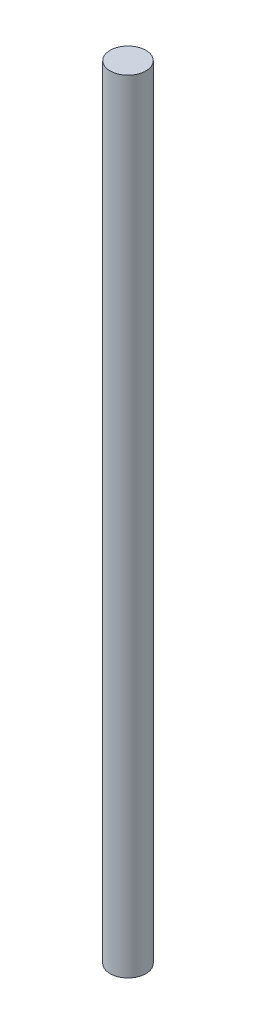
SolidWorks part; units mm, degrees
ref_plane "Front Plane" through (0, 0, 0) normal (0, 0, 1) x (1, 0, 0)
ref_plane "Top Plane" through (0, 0, 0) normal (0, 1, 0) x (1, 0, 0)
ref_plane "Right Plane" through (0, 0, 0) normal (1, 0, 0) x (0, 0, -1)
sketch "Sketch1" plane through (0, 0, 0) normal (0, 1, 0) x (1, 0, 0)
  circle A0 centre (0, 0) radius 4
  dimension "D1" = 8
extrude "Boss-Extrude1" add sketch "Sketch1" along normal blind 175
